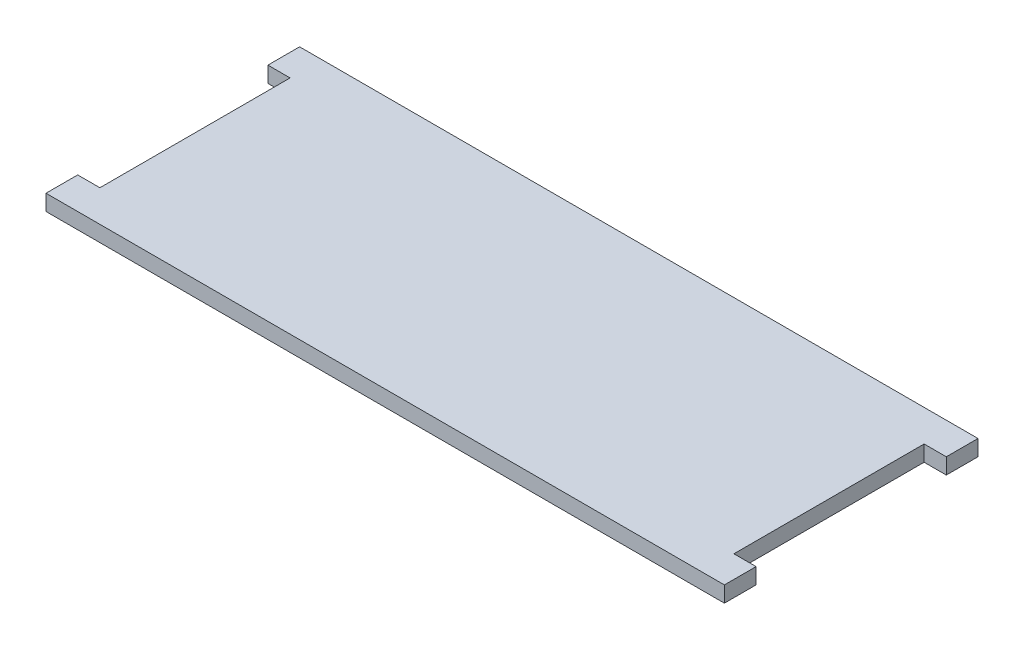
SolidWorks part; units mm, degrees
ref_plane "Front Plane" through (0, 0, 0) normal (0, 0, 1) x (1, 0, 0)
ref_plane "Top Plane" through (0, 0, 0) normal (0, 1, 0) x (1, 0, 0)
ref_plane "Right Plane" through (0, 0, 0) normal (1, 0, 0) x (0, 0, -1)
sketch "Sketch1" plane through (0, 0, 0) normal (0, 1, 0) x (1, 0, 0)
  line L1 (-63.5, 25.4) -> (63.5, 25.4)
  line L2 (-63.5, 25.4) -> (-63.5, -25.4)
  line L3 (-63.5, -25.4) -> (63.5, -25.4)
  line L4 (63.5, 25.4) -> (63.5, -25.4)
  line L5 (-63.5, 25.4) -> (63.5, -25.4) construction
  line L6 (-63.5, -25.4) -> (63.5, 25.4) construction
  line L7 (-63.5, 25.4) -> (-67.945, 25.4)
  line L8 (-63.5, 25.4) -> (-63.5, 19.05)
  line L9 (-63.5, 19.05) -> (-67.945, 19.05)
  line L10 (-67.945, 25.4) -> (-67.945, 19.05)
  line L11 (-63.5, -25.4) -> (-67.945, -25.4)
  line L12 (-63.5, -25.4) -> (-63.5, -19.05)
  line L13 (-63.5, -19.05) -> (-67.945, -19.05)
  line L14 (-67.945, -25.4) -> (-67.945, -19.05)
  line L15 (63.5, 25.4) -> (67.945, 25.4)
  line L16 (63.5, 25.4) -> (63.5, 19.05)
  line L17 (63.5, 19.05) -> (67.945, 19.05)
  line L18 (67.945, 25.4) -> (67.945, 19.05)
  line L19 (63.5, -25.4) -> (67.945, -25.4)
  line L20 (63.5, -25.4) -> (63.5, -19.05)
  line L21 (63.5, -19.05) -> (67.945, -19.05)
  line L22 (67.945, -25.4) -> (67.945, -19.05)
  point P0 (0, 0)
  dimension "D1" = 127
  dimension "D2" = 25.4
  dimension "D3" = 6.35
  dimension "D4" = 4.445
extrude "Boss-Extrude1" add sketch "Sketch1" along normal blind 3.175 contours L4 L1 L2 L3 | L7 L10 L9 L2 | L14 L11 L2 L13 | L19 L22 L21 L4 | L18 L15 L4 L17
